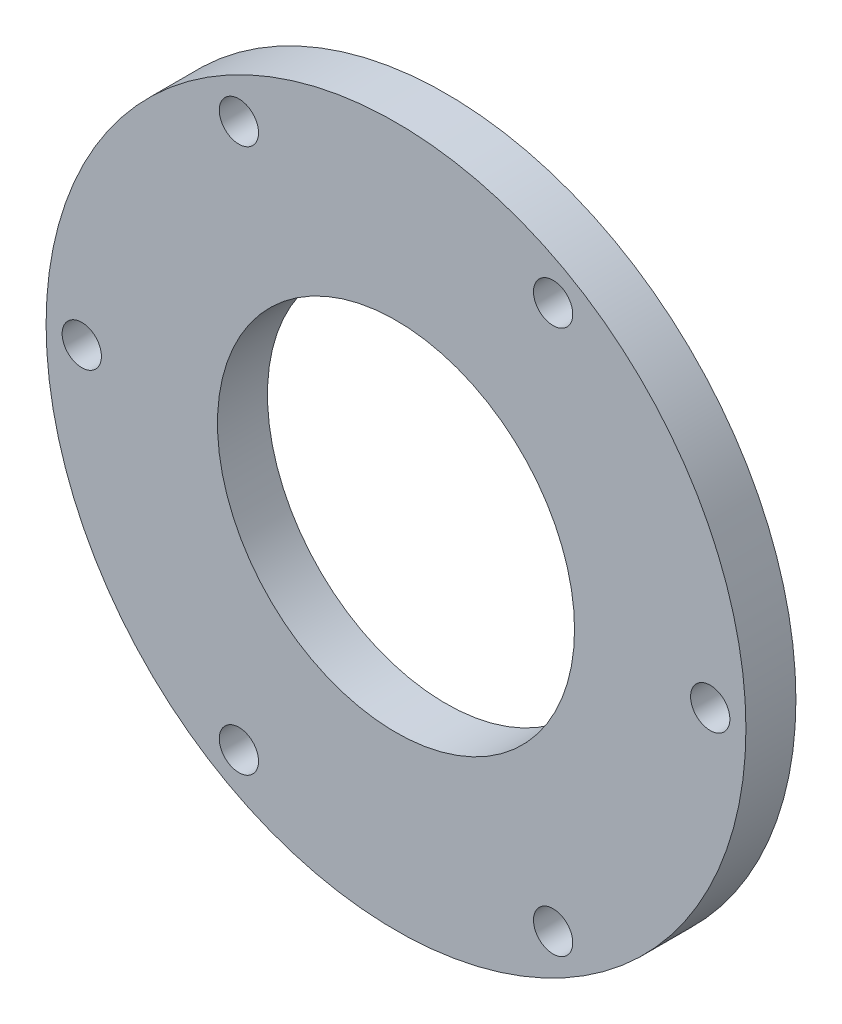
SolidWorks part; units mm, degrees
ref_plane "Płaszczyzna przednia" through (0, 0, 0) normal (0, 0, 1) x (1, 0, 0)
ref_plane "Płaszczyzna górna" through (0, 0, 0) normal (0, 1, 0) x (1, 0, 0)
ref_plane "Płaszczyzna prawa" through (0, 0, 0) normal (1, 0, 0) x (0, 0, -1)
sketch "Szkic1" plane through (0, 0, 0) normal (0, 0, 1) x (1, 0, 0)
  circle A0 centre (0, 0) radius 49
  circle A2 centre (0, 0) radius 25
  dimension "D1" = 98
  dimension "D4" = 50
extrude "Dodanie-wyciągnięcie1" add sketch "Szkic1" along normal blind 7
sketch "Szkic3" plane through (0, 0, 0) normal (0, 0, -1) x (-1, 0, 0)
  circle A0 centre (44, 0) radius 2.5
  point P0 (44, 0)
  dimension "D1" = 5
  dimension "D3" = 0
  dimension "D2" = 44
hole_wizard "Pogłębienie stożkowe pod M5 DIN965 Wkręt z łbem płaskim1" positions "Szkic3" profile "Szkic4" countersink size "M5 DIN965" standard "DIN" end condition through all
sketch "Szkic4" plane through (-44, 0, 0) normal (1, 0, 0) x (0, 1, 0)
  line L0 (0, 0) -> (0, 7)
  line L1 (0, 7) -> (2.75, 7)
  line L2 (2.75, 7) -> (2.75, 1.85)
  line L3 (2.75, 1.85) -> (4.6, 0)
  line L5 (4.6, 0) -> (0, 0)
  line L6 (-2.75, 1.85) -> (-4.6, 0) construction
  line L11 (0, -6.35) -> (0, 107.95) construction
  dimension "Średnica otworu na wylot" = 5.5
  dimension "Głębokość otworu na wylot" = 7
  dimension "Średnica zewnętrznego pogłębienia stożkowego" = 9.2
  dimension "Kąt zewnętrznego pogłębienia stożkowego" = 90
pattern_circular "Szyk kołowy1" count 6 every 60 about axis through (0, 0, 0) along (0, 0, 1) of "Pogłębienie stożkowe pod M5 DIN965 Wkręt z łbem płaskim1"
sketch "Szkic5" plane through (0, 0, 0) normal (0, 0, -1) x (-1, 0, 0)
  circle A0 centre (23.6, 23.6) radius 3.3
  circle A1 centre (23.6, -23.6) radius 3.3
  circle A2 centre (-23.6, 23.6) radius 3.3
  circle A3 centre (-23.6, -23.6) radius 3.3
  dimension "D1" = 6.6
  dimension "D4" = 6.6
  dimension "D7" = 6.6
  dimension "D10" = 6.6
  dimension "D2" = 23.6
  dimension "D3" = 23.6
  dimension "D5" = 23.6
  dimension "D6" = 23.6
  dimension "D8" = 23.6
  dimension "D9" = 23.6
  dimension "D11" = 23.6
  dimension "D12" = 23.6
extrude "Wytnij-wyciągnięcie1" cut sketch "Szkic5" against normal blind 6
